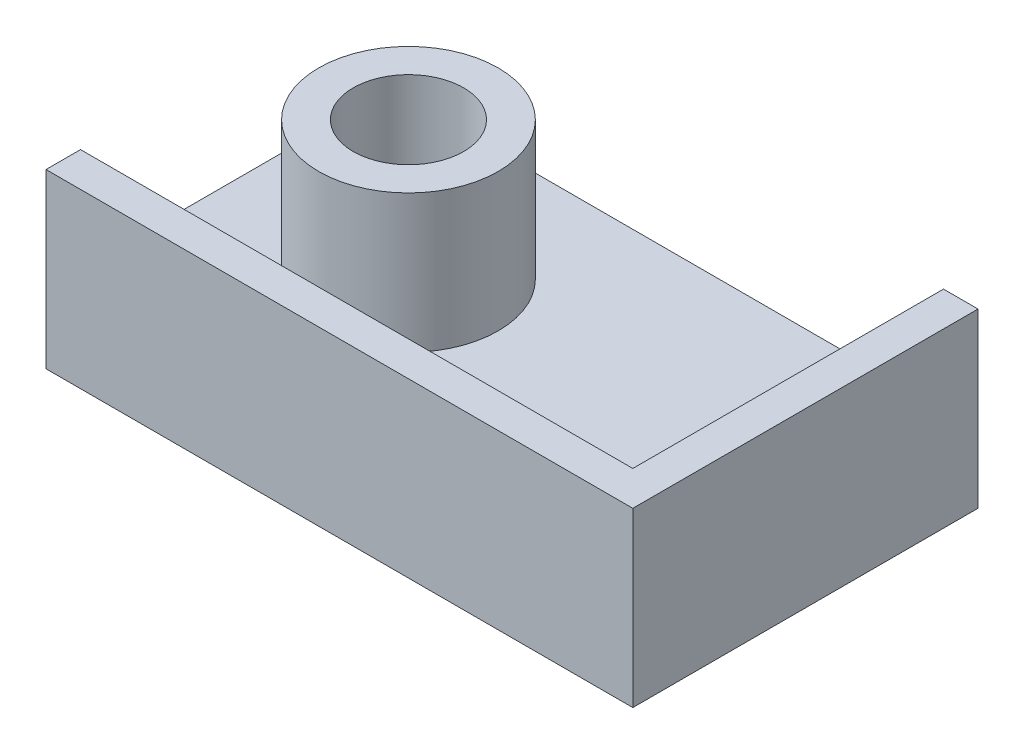
SolidWorks part; units mm, degrees
ref_plane "前视基准面" through (0, 0, 0) normal (0, 0, 1) x (1, 0, 0)
ref_plane "上视基准面" through (0, 0, 0) normal (0, 1, 0) x (1, 0, 0)
ref_plane "右视基准面" through (0, 0, 0) normal (1, 0, 0) x (0, 0, -1)
other "Configuration Table"
sketch "草图1" plane through (0, 0, 0) normal (0, 1, 0) x (1, 0, 0)
  line L1 (-8, -4.5) -> (8, -4.5)
  line L2 (-8, -4.5) -> (-8, 4.5)
  line L3 (-8, 4.5) -> (8, 4.5)
  line L4 (8, -4.5) -> (8, 4.5)
  line L5 (-8, -4.5) -> (8, 4.5) construction
  line L6 (-8, 4.5) -> (8, -4.5) construction
  point P0 (0, 0)
  dimension "D1" = 16
  dimension "D2" = 9
extrude "凸台-拉伸1" add sketch "草图1" along normal blind 2
sketch "草图2" plane through (0, 2, 0) normal (0, 1, 0) x (1, 0, 0)
  line L0 (-8, 0) -> (8, 0) construction
  line L1 (-8, 4.5) -> (-8, -4.5) construction
  line L2 (8, -4.5) -> (8, 4.5) construction
  circle A0 centre (-3, 0) radius 2.6
  dimension "D1" = 5
  dimension "D2" = 5.2
extrude "凸台-拉伸2" add sketch "草图2" along normal blind 4
sketch "草图3" plane through (0, 2, 0) normal (0, 1, 0) x (1, 0, 0)
  line L0 (-8, -4.5) -> (-8, -5.5)
  line L1 (-8, -5.5) -> (9, -5.5)
  line L2 (9, -5.5) -> (9, 4.5)
  line L3 (9, 4.5) -> (8, 4.5)
  line L4 (8, 4.5) -> (8, -4.5)
  line L5 (-8, -4.5) -> (8, -4.5) construction
  line L6 (8, -4.5) -> (8, 4.5) construction
  line L7 (8, -4.5) -> (-8, -4.5)
  dimension "D1" = 1
  dimension "D2" = 1
extrude "凸台-拉伸3" add sketch "草图3" along normal blind 3 and the other way up to surface (2 mm away) other way up to face at (0, 0, 0)
sketch "草图4" plane through (0, 6, 0) normal (0, 1, 0) x (1, 0, 0)
  circle A0 centre (-3, 0) radius 1.6
  dimension "D1" = 3.2
extrude "切除-拉伸1" cut sketch "草图4" against normal through all
